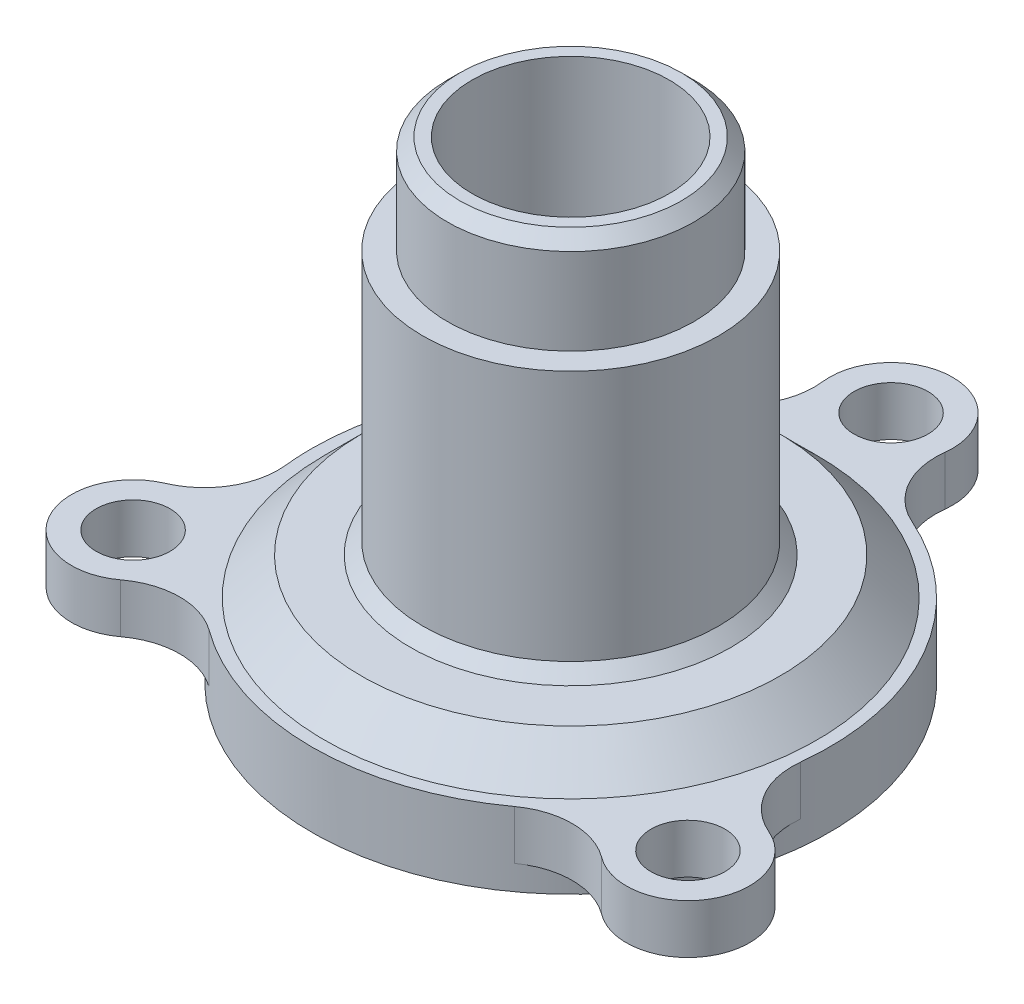
SolidWorks part; units mm, degrees
material "6061 合金"
ref_plane "前视基准面" through (0, 0, 0) normal (0, 0, 1) x (1, 0, 0)
ref_plane "上视基准面" through (0, 0, 0) normal (0, 1, 0) x (1, 0, 0)
ref_plane "右视基准面" through (0, 0, 0) normal (1, 0, 0) x (0, 0, -1)
sketch "草图1" plane through (0, 0, 0) normal (0, 0, 1) x (1, 0, 0)
  line L0 (10.5, 0) -> (15.5, 0)
  line L6 (4, 18.2) -> (5, 18.2)
  line L7 (6, 14.2) -> (6, 3.5)
  line L8 (15.5, 2) -> (10, 2)
  line L9 (0, 18.9) -> (0, 0) construction
  line L12 (15.5, 0) -> (15.5, 2)
  line L15 (10.5, 0) -> (10.5, -1)
  line L16 (10.5, -1) -> (9.5, -1)
  line L17 (5, 18.2) -> (5, 14.2)
  line L18 (5, 14.2) -> (6, 14.2)
  line L19 (4, 18.2) -> (4, 1.5)
  line L20 (9.5, -1) -> (9.5, 0.5)
  line L21 (8.5, 1.5) -> (4, 1.5)
  line L22 (6, 3.5) -> (8.5, 3.5)
  line L23 (8.5, 3.5) -> (10, 2)
  line L24 (8.5, 1.5) -> (9.5, 0.5)
  dimension "D1" = 31
  dimension "D2" = 2
  dimension "D3" = 12
  dimension "D4" = 1
  dimension "D5" = 21
  dimension "D6" = 14.2
  dimension "D7" = 10
  dimension "D8" = 4
  dimension "D9" = 8
  dimension "D10" = 1
  dimension "D11" = 2.5
  dimension "D12" = 2
  dimension "D13" = 135
  dimension "D14" = 20
  dimension "D15" = 1
  dimension "D16" = 1
revolve "旋转1" add sketch "草图1" angle 360 about L9
chamfer "倒角1" distance 0.5 angle 45 2 edges at (-5, 18.2, 0) (-6, 3.5, 0)
chamfer "倒角2" [suppressed] distance 2.5 angle 45
sketch "草图2" plane through (0, 2, 0) normal (0, 1, 0) x (1, 0, 0)
  circle A0 centre (0, 13) radius 1.5
  circle A3 centre (11.2583, -6.5) radius 1.5
  circle A4 centre (-11.2583, -6.5) radius 1.5
  circle A6 centre (0, 0) radius 13 construction
  circle A7 centre (0, 0) radius 15.5
  circle A9 centre (0, 0) radius 15.5 construction
  arc A10 (2.4823, 12.7028) -> (-2.4823, 12.7028) centre (0, 13) ccw
  circle A11 centre (0, 0) radius 10.5 construction
  arc A12 (-4.2474, 9.6026) -> (-10.4398, -1.1229) centre (0, 0) ccw
  arc A13 (4.2474, 9.6026) -> (2.4823, 12.7028) centre (5.461, 12.3462) cw
  arc A14 (-4.2474, 9.6026) -> (-2.4823, 12.7028) centre (-5.461, 12.3462) ccw
  arc A15 (10.4398, -1.1229) -> (4.2474, 9.6026) centre (0, 0) ccw
  arc A16 (10.4398, -1.1229) -> (12.2421, -4.2017) centre (13.4226, -1.4437) ccw
  arc A17 (9.7598, -8.5011) -> (12.2421, -4.2017) centre (11.2583, -6.5) ccw
  arc A18 (6.1923, -8.4797) -> (9.7598, -8.5011) centre (7.9616, -10.9024) cw
  arc A19 (-6.1923, -8.4797) -> (6.1923, -8.4797) centre (0, 0) ccw
  arc A20 (-6.1923, -8.4797) -> (-9.7598, -8.5011) centre (-7.9616, -10.9024) ccw
  arc A21 (-12.2421, -4.2017) -> (-9.7598, -8.5011) centre (-11.2583, -6.5) ccw
  arc A22 (-10.4398, -1.1229) -> (-12.2421, -4.2017) centre (-13.4226, -1.4437) cw
  circle M6 centre (0, 0) radius 15.5
  circle M12 centre (0, 0) radius 10
  dimension "D2" = 2.5
  dimension "D3" = 3
  dimension "D4" = 3
  dimension "D5" = 2.5
  dimension "D6" = 31
  dimension "D1" = 3
extrude "切除-拉伸1" cut sketch "草图2" against normal through all contours A22 A14 A10 A21 M12 M6 | A17 A7 A10 A13 A16 M12 | A21 A7 A17 A18 A20 M12 | A0 | A4 | A3
